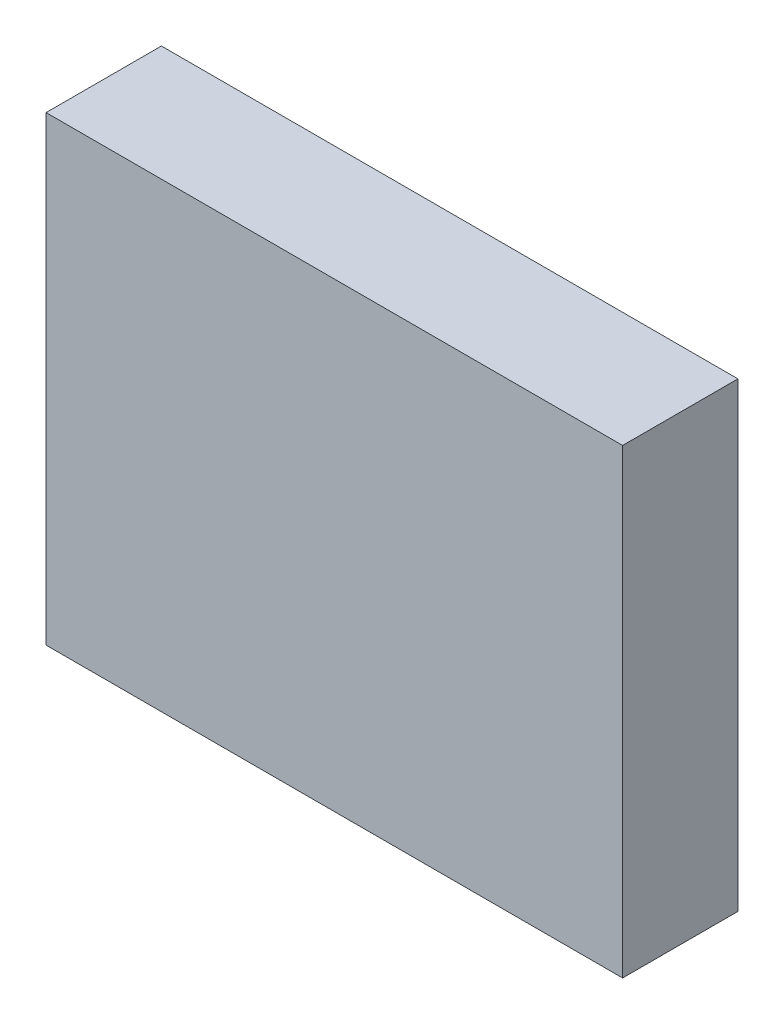
SolidWorks part; units mm, degrees
ref_plane "前视基准面" through (0, 0, 0) normal (0, 0, 1) x (1, 0, 0)
ref_plane "上视基准面" through (0, 0, 0) normal (0, 1, 0) x (1, 0, 0)
ref_plane "右视基准面" through (0, 0, 0) normal (1, 0, 0) x (0, 0, -1)
other "Configuration Table"
sketch "草图1" plane through (0, 0, 0) normal (0, 0, 1) x (1, 0, 0)
  line L1 (-50, -40) -> (50, -40)
  line L2 (-50, -40) -> (-50, 40)
  line L3 (-50, 40) -> (50, 40)
  line L4 (50, -40) -> (50, 40)
  line L5 (-50, -40) -> (50, 40) construction
  line L6 (-50, 40) -> (50, -40) construction
  point P0 (0, 0)
extrude "凸台-拉伸1" add sketch "草图1" along normal blind 20
